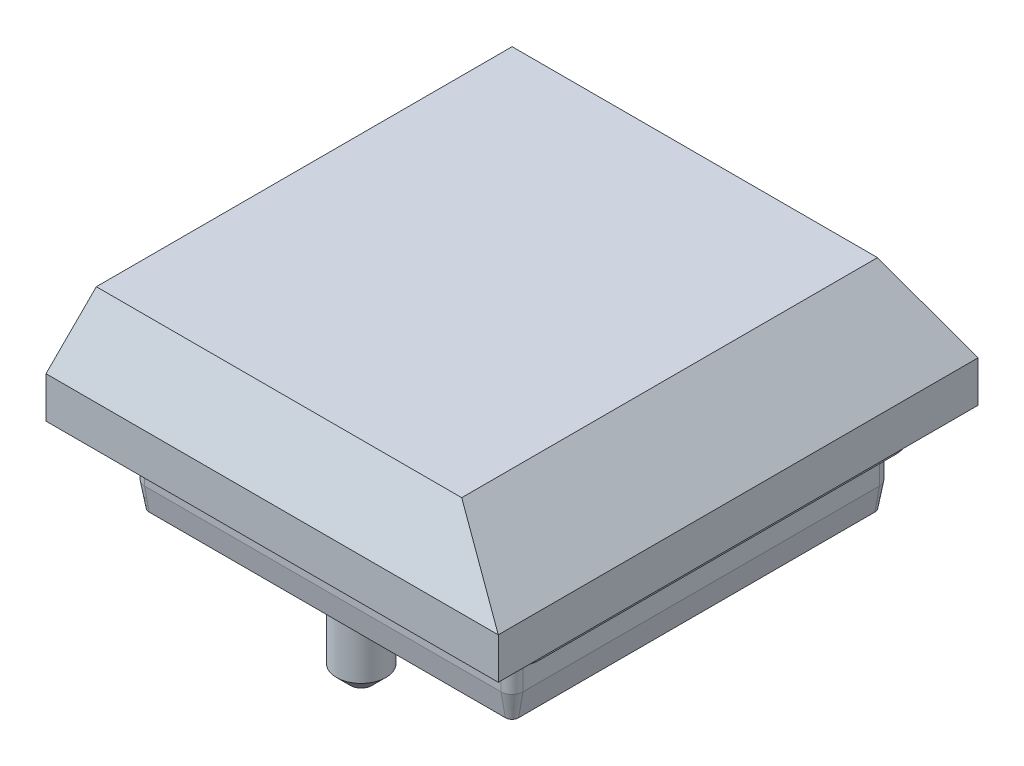
SolidWorks part; units mm, degrees
ref_plane "Front plane" through (0, 0, 0) normal (0, 0, 1) x (1, 0, 0)
ref_plane "Top plane" through (0, 0, 0) normal (0, 1, 0) x (1, 0, 0)
ref_plane "Right plane" through (0, 0, 0) normal (1, 0, 0) x (0, 0, -1)
sketch "Sketch1" plane through (0, 0, 0) normal (0, 1, 0) x (1, 0, 0)
  line L1 (-6.5, -7.5) -> (6.5, -7.5)
  line L2 (-7.5, -6.5) -> (-7.5, 6.5)
  line L3 (-6.5, 7.5) -> (6.5, 7.5)
  line L4 (7.5, -6.5) -> (7.5, 6.5)
  line L5 (-7.5, -7.5) -> (7.5, 7.5) construction
  line L6 (-7.5, 7.5) -> (7.5, -7.5) construction
  arc A0 (-7.5, 6.5) -> (-6.5, 7.5) centre (-6.5, 6.5) cw
  arc A1 (6.5, 7.5) -> (7.5, 6.5) centre (6.5, 6.5) cw
  arc A2 (6.5, -7.5) -> (7.5, -6.5) centre (6.5, -6.5) ccw
  arc A3 (-6.5, -7.5) -> (-7.5, -6.5) centre (-6.5, -6.5) cw
  point P0 (0, 0)
  dimension "D2" = 1
  dimension "D1" = 15
extrude "Boss-Extrude1" add sketch "Sketch1" along normal blind 0.8 contours L1 A2 L4 A1 L3 A0 L2 A3
sketch "Sketch2" plane through (0, 0, 0) normal (0, -1, 0) x (1, 0, 0)
  line L8 (-6.9, 6.5) -> (-6.9, -6.5)
  line L9 (-6.5, -6.9) -> (6.5, -6.9)
  line L10 (6.9, -6.5) -> (6.9, 6.5)
  line L11 (6.5, 6.9) -> (-6.5, 6.9)
  line L12 (-6.9, 6.5) -> (-6.9, -6.5)
  line L13 (-6.5, -6.9) -> (6.5, -6.9)
  line L14 (6.9, -6.5) -> (6.9, 6.5)
  line L15 (6.5, 6.9) -> (-6.5, 6.9)
  arc A8 (-6.5, 6.9) -> (-6.9, 6.5) centre (-6.5, 6.5) ccw
  arc A9 (-6.9, -6.5) -> (-6.5, -6.9) centre (-6.5, -6.5) ccw
  arc A10 (6.5, -6.9) -> (6.9, -6.5) centre (6.5, -6.5) ccw
  arc A11 (6.9, 6.5) -> (6.5, 6.9) centre (6.5, 6.5) ccw
  arc A12 (-6.5, 6.9) -> (-6.9, 6.5) centre (-6.5, 6.5) ccw
  arc A13 (-6.9, -6.5) -> (-6.5, -6.9) centre (-6.5, -6.5) ccw
  arc A14 (6.5, -6.9) -> (6.9, -6.5) centre (6.5, -6.5) ccw
  arc A15 (6.9, 6.5) -> (6.5, 6.9) centre (6.5, 6.5) ccw
  dimension "D1" = 0.6
extrude "Boss-Extrude2" add sketch "Sketch2" along normal blind 1.3
sketch "Sketch3" plane through (0, -1.3, 0) normal (0, -1, 0) x (1, 0, 0)
  line L4 (-6.9, 6.5) -> (-6.9, -6.5)
  line L5 (-6.5, -6.9) -> (6.5, -6.9)
  line L6 (6.9, -6.5) -> (6.9, 6.5)
  line L7 (6.5, 6.9) -> (-6.5, 6.9)
  line L8 (-6.9, 6.5) -> (-6.9, -6.5)
  line L9 (-6.5, -6.9) -> (6.5, -6.9)
  line L10 (6.9, -6.5) -> (6.9, 6.5)
  line L11 (6.5, 6.9) -> (-6.5, 6.9)
  arc A4 (-6.5, 6.9) -> (-6.9, 6.5) centre (-6.5, 6.5) ccw
  arc A5 (-6.9, -6.5) -> (-6.5, -6.9) centre (-6.5, -6.5) ccw
  arc A6 (6.5, -6.9) -> (6.9, -6.5) centre (6.5, -6.5) ccw
  arc A7 (6.9, 6.5) -> (6.5, 6.9) centre (6.5, 6.5) ccw
  arc A8 (-6.5, 6.9) -> (-6.9, 6.5) centre (-6.5, 6.5) ccw
  arc A9 (-6.9, -6.5) -> (-6.5, -6.9) centre (-6.5, -6.5) ccw
  arc A10 (6.5, -6.9) -> (6.9, -6.5) centre (6.5, -6.5) ccw
  arc A11 (6.9, 6.5) -> (6.5, 6.9) centre (6.5, 6.5) ccw
  dimension "D1" = 0
extrude "Boss-Extrude3" add sketch "Sketch3" along normal blind 0.9 draft 10
sketch "Sketch4" plane through (0, -2.2, 0) normal (0, -1, 0) x (1, 0, 0)
  line L0 (-5.9, 0) -> (6.1513, 0) construction
  circle A0 centre (0, 0) radius 1.6
  circle A1 centre (0, -5.5) radius 0.9
  circle A5 centre (0, 5.5) radius 0.9
  dimension "D1" = 3.2
  dimension "D2" = 1.8
  dimension "D3" = 5.5
extrude "Boss-Extrude4" add sketch "Sketch4" along normal blind 2.65
sketch "Sketch5" plane through (0, -2.2, 0) normal (0, -1, 0) x (1, 0, 0)
  circle A0 centre (-5.9, 0) radius 0.6
  circle A1 centre (-3.8, -5) radius 0.6
  dimension "D1" = 1.2
  dimension "D2" = 3.8
  dimension "D3" = 5.9
  dimension "D4" = 5
extrude "Boss-Extrude5" add sketch "Sketch5" along normal blind 3
chamfer "Chamfer1" distance 0.5 angle 40 2 edges at (-3.8, -5.2, -5.6) (-5.9, -5.2, -0.6)
chamfer "Chamfer2" distance 0.5 angle 45 3 edges at (0, -4.85, -6.4) (0, -4.85, -1.6) (0, -4.85, 6.4)
sketch "Sketch6" plane through (0, 0.8, 0) normal (0, 1, 0) x (1, 0, 0)
  line L1 (8.25, 8.75) -> (-8.25, 8.75)
  line L2 (8.25, 8.75) -> (8.25, -8.75)
  line L3 (8.25, -8.75) -> (-8.25, -8.75)
  line L4 (-8.25, 8.75) -> (-8.25, -8.75)
  line L5 (8.25, 8.75) -> (-8.25, -8.75) construction
  line L6 (8.25, -8.75) -> (-8.25, 8.75) construction
  point P0 (0, 0)
  dimension "D1" = 16.5
  dimension "D2" = 17.5
extrude "Boss-Extrude6" add sketch "Sketch6" along normal blind 4
chamfer "Chamfer3" distance 2.5 angle 45 1 edges at (8.25, 4.8, 0)
chamfer "Chamfer4" distance 2.5 angle 25 2 edges at (-1.25, 4.8, -8.75) (-1.25, 4.8, 8.75)
chamfer "Chamfer5" distance 2.5 angle 15 1 edges at (-8.25, 4.8, 0)
ref_plane "Vertical" through (0, 0, 0) normal (0, 0, 1) x (1, 0, 0)
ref_plane "Horisontal" through (0, 0, 0) normal (1, 0, 0) x (0, 0, -1)
